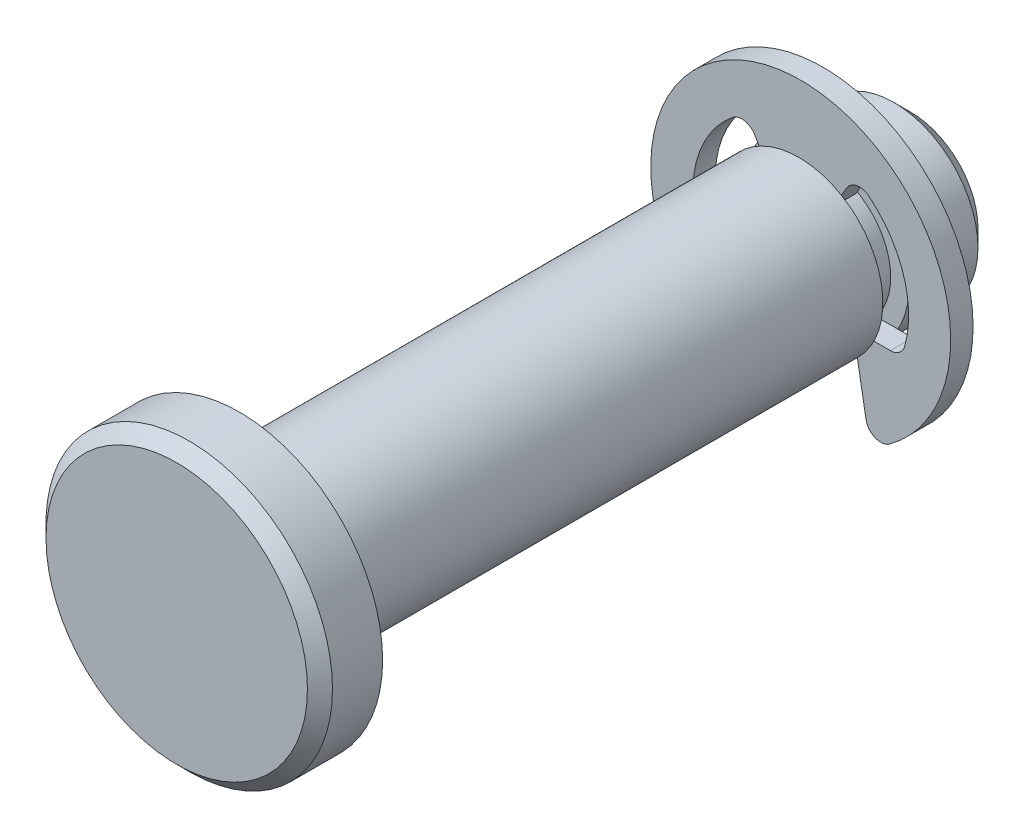
SolidWorks part; units mm, degrees
material "Plain Carbon Steel"
ref_plane "Front" through (0, 0, 0) normal (0, 0, 1) x (1, 0, 0)
ref_plane "Top" through (0, 0, 0) normal (0, 1, 0) x (1, 0, 0)
ref_plane "Right" through (0, 0, 0) normal (1, 0, 0) x (0, 0, -1)
sketch "Sketch2" plane through (0, 0, 0) normal (0, 0, 1) x (1, 0, 0)
  circle A0 centre (0, 0) radius 2.3813
  point P3 (0, 2.3813)
  point P4 (0, -2.3813)
  dimension "dia" = 4.7625
extrude "Extrude1" add sketch "Sketch2" along normal mid plane 19.05
sketch "Sketch3" plane through (0, 0, 0) normal (1, 0, 0) x (0, 0, -1)
  line L0 (9.525, 2.3813) -> (-9.525, 2.3813) construction
  line L1 (6.35, 2.3812) -> (7.0866, 2.3813)
  line L2 (6.35, 2.3812) -> (6.35, 1.8669)
  line L3 (6.35, 1.8669) -> (7.0866, 1.8669)
  line L4 (7.0866, 2.3813) -> (7.0866, 1.8669)
  line L5 (-9.525, 2.3813) -> (-9.525, -2.3813) construction
  line L10 (7.0866, 1.8669) -> (7.0866, -1.8669) construction
  point P11 (7.0866, 0)
  point P14 (6.7183, 2.3813)
  dimension "groove wd" = 0.7366
  dimension "groove dia" = 3.7338
  dimension "usable lg" = 15.875
revolve "Cut-Revolve1" cut sketch "Sketch3" angle 360 about axis through (0, 0, 9.525) along (0, 0, -1)
sketch "Sketch8" plane through (0, 0, 9.525) normal (0, 0, 1) x (1, 0, 0)
  circle A0 centre (0, 0) radius 4.064
  dimension "head dia" = 8.128
extrude "Extrude6" add sketch "Sketch8" along normal blind 1.778
chamfer "Chamfer2" distance 0.3556 angle 45 1 edges at (4.064, 0, 11.303)
ref_plane "Plane1" through (0, 0, -6.7183) normal (0, 0, 1) x (1, 0, 0)
sketch "Sketch4" plane through (0, 0, -6.7183) normal (0, 0, 1) x (1, 0, 0)
  line L0 (0, 1.8669) -> (0, -1.8669) construction
  circle A0 centre (0, 0) radius 4.2545
  circle A1 centre (0, 0) radius 1.8669
  dimension "ring dia" = 8.509
extrude "Extrude2" add sketch "Sketch4" along normal mid plane 0.635 separate body
sketch "Sketch5" plane through (0, 0, 0) normal (0, 0, 1) x (1, 0, 0)
  line L0 (0, 4.2545) -> (0, 1.8669) construction
  line L1 (-1.5304, 2.6506) -> (0, 0)
  line L2 (-2.8484, -1.1201) -> (-1.4935, -1.1201)
  line L3 (0, 0) -> (1.5304, 2.6506)
  line L4 (-1.4935, -1.1201) -> (-1.9617, -3.7753)
  line L5 (1.4935, -1.1201) -> (1.9617, -3.7753)
  line L6 (1.4935, -1.1201) -> (2.8484, -1.1201)
  arc A0 (-1.5304, 2.6506) -> (-2.8484, -1.1201) centre (0, 0) ccw
  circle A1 centre (0, 0) radius 4.2545 construction
  circle A2 centre (0, 0) radius 1.8669 construction
  arc A3 (2.8484, -1.1201) -> (1.5304, 2.6506) centre (0, 0) ccw
  arc A4 (-1.9617, -3.7753) -> (1.9617, -3.7753) centre (0, 0) ccw
  circle A5 centre (0, 0) radius 1.8669 construction
  point P10 (0, 3.0607)
  dimension "D1" = 30
  dimension "D2" = 10
  dimension "D3" = 1.1201
extrude "Extrude4" cut sketch "Sketch5" against normal through all
sketch "Sketch6" plane through (0, 0, -6.4008) normal (0, 0, 1) x (1, 0, 0)
  line L0 (-0.9335, 1.6168) -> (0.9335, 1.6168)
  circle A0 centre (0, 0) radius 1.8669 construction
  arc A1 (0.9335, 1.6168) -> (-0.9335, 1.6168) centre (0, 0) ccw
extrude "Extrude5" add sketch "Sketch6" against normal up to surface (0.635 mm away) up to face at (0, 0.5273, -7.0358)
fillet "Fillet1" radius 0.4254 6 edges at (1.9617, -3.7753, -6.7183) (-1.9617, -3.7753, -6.7183) (2.8484, -1.1201, -6.7183) (1.5304, 2.6506, -6.7183) (-1.5304, 2.6506, -6.7183) (-2.8484, -1.1201, -6.7183)
chamfer "Chamfer1" distance 0.4763 angle 45 1 edges at (2.3813, 0, -9.525)
sketch "Sketch7" plane through (0, 0, 0) normal (1, 0, 0) x (0, 0, -1)
  line L0 (7.0358, 4.2545) -> (6.4008, 4.2545) construction
  line L1 (9.525, -2.3813) -> (9.525, 2.3813) construction
  line L2 (6.4008, -3.5079) -> (7.0358, -3.5079) construction
  line L3 (-11.303, 3.7084) -> (-11.303, -3.7084) construction
  point P0 (7.0866, -3.5079)
  point P1 (9.525, 2.3813)
  point P2 (-11.303, 4.064)
  point P6 (6.35, 4.2545)
  point P7 (9.525, -2.3813)
  point P12 (-9.525, 4.064)
  point P16 (6.35, -3.5079)
equation "\"D1@Chamfer1\" = \"dia@Sketch2\" * .1"
equation "\"D1@Fillet1\" = \"ring dia@Sketch4\" * .05"
equation "\"D3@Sketch5\" = \"groove dia@Sketch3\" * .3"
equation "\"D1@Chamfer2\" = \"head ht@Extrude6\" * .2"
